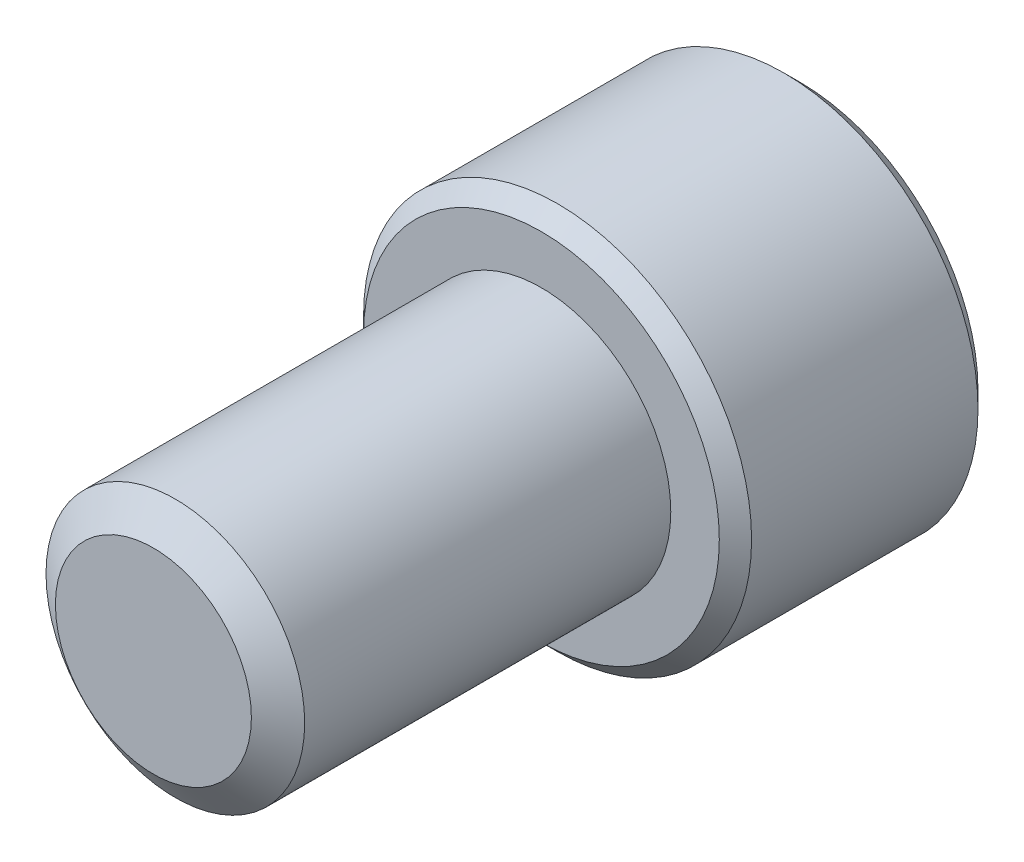
SolidWorks part; units mm, degrees
ref_plane "Front Plane" through (0, 0, 0) normal (0, 0, 1) x (1, 0, 0)
ref_plane "Top Plane" through (0, 0, 0) normal (0, 1, 0) x (1, 0, 0)
ref_plane "Right Plane" through (0, 0, 0) normal (1, 0, 0) x (0, 0, -1)
sketch "Sketch1" plane through (0, 0, 0) normal (0, 0, 1) x (1, 0, 0)
  circle A0 centre (0, 0) radius 3.175
  dimension "D1" = 6.35
extrude "Boss-Extrude1" add sketch "Sketch1" along normal blind 9.525
sketch "Sketch2" plane through (0, 0, 0) normal (1, 0, 0) x (0, 0, -1)
  line L0 (-9.525, 3.175) -> (-9.525, 2.4054)
  line L1 (-9.525, 3.175) -> (-9.525, -3.175) construction
  line L2 (-9.525, 2.4054) -> (-8.9862, 3.175)
  line L3 (0, 3.175) -> (-9.525, 3.175) construction
  line L4 (-8.9862, 3.175) -> (-9.525, 3.175)
  line L5 (0, 0) -> (-9.525, 0) construction
  dimension "D1" = 0.7696
  dimension "D2" = 55
revolve "Cut-Revolve1" cut sketch "Sketch2" angle 360 about L5
sketch "Sketch3" plane through (0, 0, 0) normal (0, 0, 1) x (1, 0, 0)
  circle A0 centre (0, 0) radius 4.7625
  dimension "D1" = 9.525
extrude "Boss-Extrude2" add sketch "Sketch3" against normal blind 6.35
sketch "Sketch4" plane through (0, 0, 0) normal (0, 0, 1) x (1, 0, 0)
  line L1 (0, -2.7496) -> (2.3812, -1.3748)
  line L2 (2.3812, -1.3748) -> (2.3813, 1.3748)
  line L3 (2.3813, 1.3748) -> (0, 2.7496)
  line L4 (0, 2.7496) -> (-2.3812, 1.3748)
  line L5 (-2.3812, 1.3748) -> (-2.3812, -1.3748)
  line L6 (-2.3812, -1.3748) -> (0, -2.7496)
  circle A0 centre (0, 0) radius 2.3813 construction
  dimension "D1" = 4.7625
extrude "Cut-Extrude1" cut sketch "Sketch4" along normal blind 3.5719 from surface at -6.35 starting at face at (4.7625, 0, -6.35)
sketch "Sketch5" plane through (0, 0, -6.35) normal (0, 0, -1) x (-1, 0, 0)
  circle A0 centre (0, 0) radius 2.7496
extrude "Cut-Extrude2" cut sketch "Sketch5" against normal through all draft 45
chamfer "Chamfer1" distance 0.3962 angle 45 2 edges at (4.7625, 0, 0) (4.7625, 0, -6.35)
sketch "Sketch6" [suppressed] plane through (0, 0, 0) normal (1, 0, 0) x (0, 0, -1)
  line L0 (0, 3.175) -> (0, 6.7437)
  line L1 (0, 3.175) -> (-4.6018, 3.175)
  line L2 (0, 6.7437) -> (-0.2045, 6.7437)
  line L3 (-0.2045, 6.7437) -> (-4.0894, 3.3666)
  line L4 (0, 3.175) -> (-8.9862, 3.175) construction
  line L5 (0, 0) -> (-9.525, 0) construction
  line L6 (0, -3.175) -> (0, 3.175) construction
  line L7 (-9.525, 2.4054) -> (-9.525, -2.4054) construction
  arc A0 (-4.6018, 3.175) -> (-4.0894, 3.3666) centre (-4.6018, 3.956) ccw
  point P4 (0, 0)
  dimension "D1" = 6.7437
  dimension "D2" = 0.2045
  dimension "D3" = 4.0894
  dimension "D4" = 41
revolve "Revolve1" [suppressed] add sketch "Sketch6" angle 360 about L5
sketch "Sketch7" [suppressed] plane through (0, 0, 0) normal (0, 0, -1) x (-1, 0, 0)
  line L1 (-1.9844, -1.1457) -> (0, -2.2914)
  line L2 (0, -2.2914) -> (1.9844, -1.1457)
  line L3 (1.9844, -1.1457) -> (1.9844, 1.1457)
  line L4 (1.9844, 1.1457) -> (0, 2.2914)
  line L5 (0, 2.2914) -> (-1.9844, 1.1457)
  line L6 (-1.9844, 1.1457) -> (-1.9844, -1.1457)
  circle A0 centre (0, 0) radius 1.9844 construction
  dimension "D1" = 3.9688
extrude "Cut-Extrude3" [suppressed] cut sketch "Sketch7" against normal blind 2.8626
sketch "Sketch8" [suppressed] plane through (0, 0, 0) normal (0, 0, -1) x (-1, 0, 0)
  circle A0 centre (0, 0) radius 2.2914
extrude "Cut-Extrude4" [suppressed] cut sketch "Sketch8" against normal through all draft 45
sketch "Sketch10" [suppressed] plane through (0, 0, 0) normal (1, 0, 0) x (0, 0, -1)
  line L0 (0, 0) -> (0, 5.5499)
  line L1 (0, 5.5499) -> (0.4536, 5.5499)
  line L2 (0, 0) -> (0.866, 0)
  line L3 (0.866, 0) -> (2.0117, 1.9844)
  line L4 (2.0117, 1.9844) -> (3.3528, 1.9844)
  line L5 (3.3528, 1.9844) -> (3.3528, 2.7781)
  line L6 (0, 0) -> (-4.1183, 0) construction
  arc A1 (0.4536, 5.5499) -> (3.3528, 2.7781) centre (-2.0778, 0) cw
  dimension "D1" = 0.4536
  dimension "D2" = 5.5499
  dimension "D3" = 0.866
  dimension "D4" = 120
  dimension "D5" = 1.9844
  dimension "D6" = 2.7781
  dimension "D7" = 1.3411
revolve "Revolve2" [suppressed] add sketch "Sketch10" angle 360 about L6
sketch "Sketch11" [suppressed] plane through (0, 0, -3.3528) normal (0, 0, -1) x (-1, 0, 0)
  line L1 (-1.9844, -1.1457) -> (0, -2.2914)
  line L2 (0, -2.2914) -> (1.9844, -1.1457)
  line L3 (1.9844, -1.1457) -> (1.9844, 1.1457)
  line L4 (1.9844, 1.1457) -> (0, 2.2914)
  line L5 (0, 2.2914) -> (-1.9844, 1.1457)
  line L6 (-1.9844, 1.1457) -> (-1.9844, -1.1457)
  circle A0 centre (0, 0) radius 1.9844 construction
extrude "Cut-Extrude5" [suppressed] cut sketch "Sketch11" against normal up to vertex
sketch "Sketch12" [suppressed] plane through (0, 0, -3.3528) normal (0, 0, -1) x (-1, 0, 0)
  circle A0 centre (0, 0) radius 2.2914
extrude "Cut-Extrude6" [suppressed] cut sketch "Sketch12" against normal through all draft 45
sketch "Sketch13" [suppressed] plane through (0, 0, 0) normal (1, 0, 0) x (0, 0, -1)
  line L0 (0, 0) -> (0, 4.7625)
  line L1 (0, -3.175) -> (0, 3.175) construction
  line L2 (0, 4.7625) -> (2.54, 4.7625)
  line L3 (2.54, 4.7625) -> (3.175, 4.1275)
  line L4 (3.175, 4.1275) -> (3.175, 0)
  line L5 (3.175, 0) -> (0, 0)
  line L6 (0, 0) -> (-6.666, 0) construction
  dimension "D1" = 3.175
  dimension "D2" = 4.7625
  dimension "D3" = 4.1275
  dimension "D4" = 2.54
revolve "Revolve3" [suppressed] add sketch "Sketch13" angle 360 about L6
sketch "Sketch14" [suppressed] plane through (0, 0, -3.175) normal (0, 0, -1) x (-1, 0, 0)
  line L1 (0, -1.8331) -> (1.5875, -0.9165)
  line L2 (1.5875, -0.9165) -> (1.5875, 0.9165)
  line L3 (1.5875, 0.9165) -> (0, 1.8331)
  line L4 (0, 1.8331) -> (-1.5875, 0.9165)
  line L5 (-1.5875, 0.9165) -> (-1.5875, -0.9165)
  line L6 (-1.5875, -0.9165) -> (0, -1.8331)
  circle A0 centre (0, 0) radius 1.5875 construction
  dimension "D1" = 3.175
extrude "Cut-Extrude7" [suppressed] cut sketch "Sketch14" against normal blind 2.3876
sketch "Sketch15" [suppressed] plane through (0, 0, -3.175) normal (0, 0, -1) x (-1, 0, 0)
  circle A0 centre (0, 0) radius 1.8331
extrude "Cut-Extrude8" [suppressed] cut sketch "Sketch15" against normal through all draft 45
equation "\"Length\"= .375"
equation "\"D1@Boss-Extrude1\"=\"Length\""
